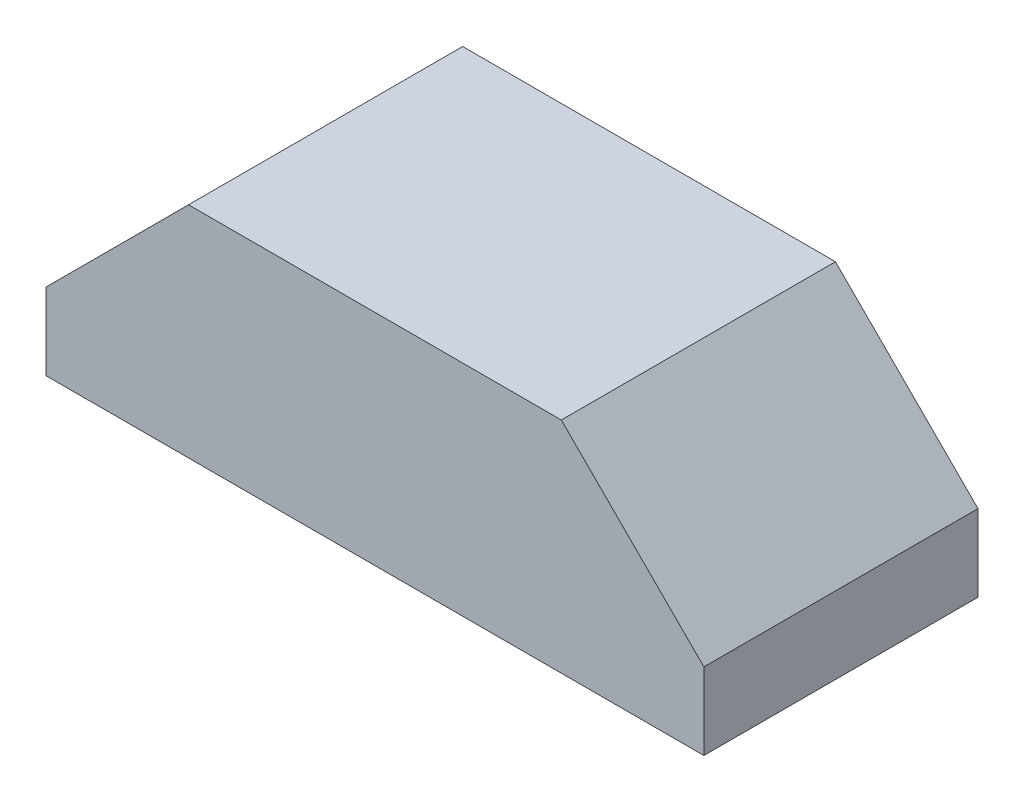
SolidWorks part; units mm, degrees
ref_plane "Ebene vorne" through (0, 0, 0) normal (0, 0, 1) x (1, 0, 0)
ref_plane "Ebene oben" through (0, 0, 0) normal (0, 1, 0) x (1, 0, 0)
ref_plane "Ebene rechts" through (0, 0, 0) normal (1, 0, 0) x (0, 0, -1)
sketch "Skizze1" plane through (0, 0, 0) normal (0, 0, 1) x (1, 0, 0)
  line L0 (0, 0) -> (0, 23680.6173) construction
  line L1 (3.4, 1.8089) -> (-3.4, 1.8089)
  line L2 (-3.4, 1.8089) -> (-6, -0.7911)
  line L3 (-6, -0.7911) -> (-6, -2.1911)
  line L4 (-6, -2.1911) -> (6, -2.1911)
  line L5 (6, -0.7911) -> (6, -2.1911)
  line L6 (3.4, 1.8089) -> (6, -0.7911)
  point P9 (0, -2.1911)
  point P11 (0, 1.8089)
  dimension "D1" = 3.4
  dimension "D2" = 6
  dimension "D3" = 4
  dimension "D4" = 135
extrude "Aufsatz-Linear austragen1" add sketch "Skizze1" along normal blind 5 contours L1 L2 L3 L4 L5 L6
